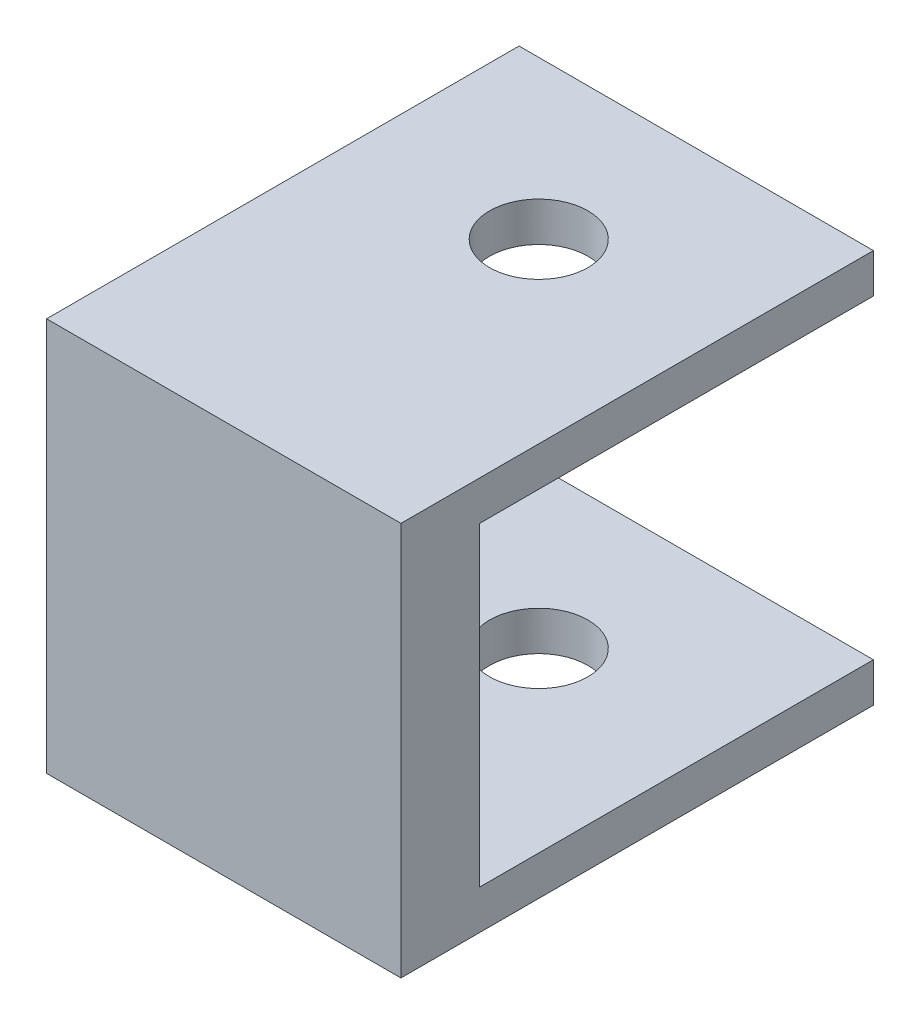
SolidWorks part; units mm, degrees
ref_plane "前视基准面" through (0, 0, 0) normal (0, 0, 1) x (1, 0, 0)
ref_plane "上视基准面" through (0, 0, 0) normal (0, 1, 0) x (1, 0, 0)
ref_plane "右视基准面" through (0, 0, 0) normal (1, 0, 0) x (0, 0, -1)
other "Configuration Table"
sketch "草图1" plane through (0, 0, 0) normal (1, 0, 0) x (0, 0, -1)
  line L0 (0, 20) -> (0, 0)
  line L1 (0, 0) -> (24, 0)
  line L2 (24, 0) -> (24, 2)
  line L3 (24, 2) -> (4, 2)
  line L4 (4, 2) -> (4, 18)
  line L5 (4, 18) -> (24, 18)
  line L6 (24, 18) -> (24, 20)
  line L7 (24, 20) -> (0, 20)
  dimension "D1" = 20
  dimension "D2" = 2
  dimension "D3" = 4
  dimension "D4" = 24
extrude "凸台-拉伸1" add sketch "草图1" along normal blind 18
sketch "草图2" plane through (0, 2, 0) normal (0, 1, 0) x (1, 0, 0)
  line L0 (18, 24) -> (0, 24) construction
  line L1 (9, 24) -> (9, 16) construction
  circle A0 centre (9, 16) radius 2.5
  point P4 (9, 15.6018)
  dimension "D2" = 5
  dimension "D1" = 8
extrude "切除-拉伸1" cut sketch "草图2" against normal blind 18 and the other way blind 37
